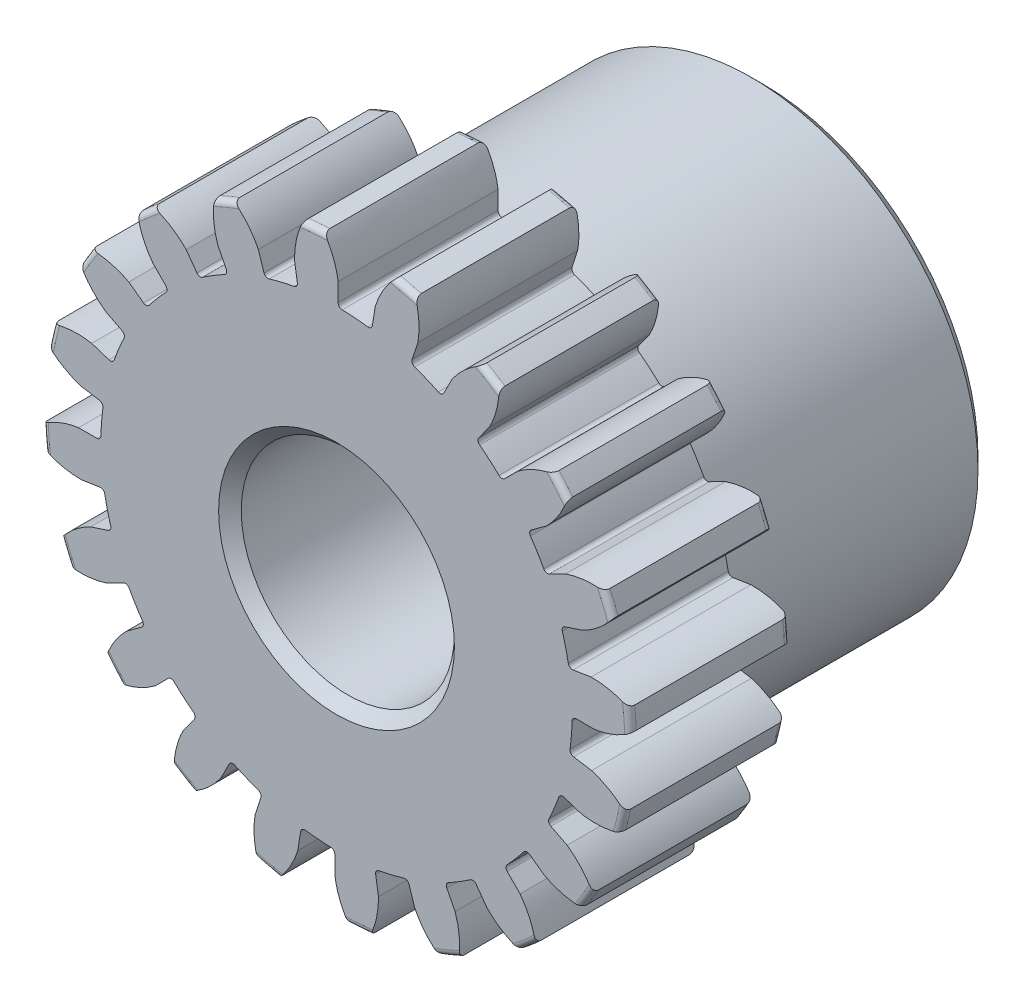
SolidWorks part; units mm, degrees
ref_plane "Front" through (0, 0, 0) normal (0, 0, 1) x (1, 0, 0)
ref_plane "Top" through (0, 0, 0) normal (0, 1, 0) x (1, 0, 0)
ref_plane "Right" through (0, 0, 0) normal (1, 0, 0) x (0, 0, -1)
sketch "Sketch1" plane through (0, 0, 0) normal (0, 0, 1) x (1, 0, 0)
  line L0 (-254, 0) -> (254, 0) construction
  circle A0 centre (0, 0) radius 8.763
  circle A1 centre (0, 0) radius 7.9375 construction
  circle A3 centre (0, 0) radius 7.0191 construction
  dimension "D1" = 0.9184
  dimension "OD" = 17.526
  dimension "Ptich Dia" = 15.875
  dimension "D2" = 1.7439
  dimension "Root Dia" = 14.0383
  dimension "D3" = 0.8255
  dimension "Number of Teeth" = 508
extrude "Boss-Extrude1" add sketch "Sketch1" against normal blind 4.7625
sketch "Sketch2" plane through (0, 0, 0) normal (1, 0, 0) x (0, 0, -1)
  line L0 (4.7625, 0) -> (12.7, 0)
  line L1 (4.7625, 0) -> (4.7625, 6.7469)
  line L2 (4.7625, 6.7469) -> (12.7, 6.7469)
  line L3 (12.7, 6.7469) -> (12.7, 0)
  point P5 (12.7, -6.7469)
  dimension "Face Wd" = 4.7625
  dimension "D Oa'll Wd" = 12.7
  dimension "B Hub Dia" = 13.4937
revolve "Revolve1" add sketch "Sketch2" angle 360 about L0
fillet "Fillet2" radius 0.1753 3 edges at (8.763, 0, -4.7625) (8.763, 0, 0) (6.7469, 0, -4.7625)
sketch "Sketch3" plane through (0, 0, 0) normal (0, 0, 1) x (1, 0, 0)
  line L0 (0, 0) -> (0, 8.763) construction
  line L1 (-1.9241, 7.4399) -> (0, 7.9375)
  line L2 (-9.5921, 7.9375) -> (9.5921, 7.9375) construction
  line L3 (-9.2865, 5.5358) -> (9.2865, 10.3392) construction
  line L4 (-1.9241, 7.4399) -> (0, 0) construction
  line L5 (-4.2708, 6.3886) -> (0, 0) construction
  line L6 (-4.2708, 6.3886) -> (-0.4919, 8.9149) construction
  line L7 (-1.3417, 7.5666) -> (0, 0) construction
  line L8 (-1.3417, 7.5666) -> (0.0282, 7.8095) construction
  arc A0 (-1.9241, 7.4399) -> (-4.2708, 6.3886) centre (0, 0) ccw
  circle A1 centre (0, 0) radius 7.9375 construction
  circle A2 centre (0, 0) radius 7.6847 construction
  arc A3 (-1.9241, 7.4399) -> (-1.3417, 7.5666) centre (0, 0) cw
  circle A4 centre (0, 0) radius 8.763 construction
  point P6 (0, 7.9375)
  dimension "D1" = 1.9874
  dimension "Pressure Angle" = 14.5
  dimension "D2" = 2.5836
  dimension "D3" = 4.5456
  dimension "D4" = 0.5962
  dimension "D5" = 1.3912
sketch "Sketch4" plane through (0, 0, 0) normal (0, 0, 1) x (1, 0, 0)
  line L0 (0, 0) -> (0.6209, 7.8886) construction
  line L1 (0.0488, 7.6845) -> (0.0488, 7.019)
  line L2 (0, 7.9375) -> (1.2417, 7.8398) construction
  line L3 (1.1539, 7.5975) -> (1.0498, 6.9402)
  line L4 (0.0488, 7.019) -> (0, 0) construction
  line L5 (0, 0) -> (0, 8.763) construction
  arc A0 (1.0498, 6.9402) -> (0.0488, 7.019) centre (0, 0) ccw
  arc A1 (0, 7.9375) -> (1.2417, 7.8398) centre (0, 0) cw construction
  circle A2 centre (0, 0) radius 7.9375 construction
  circle A3 centre (0, 0) radius 7.6847 construction
  circle A4 centre (0, 0) radius 7.0191 construction
  arc A5 (1.8804, 8.7282) -> (-0.4919, 8.9149) centre (0, 0) ccw
  spline S0 degree 2 poles (-0.4919, 8.9149) (-0.0446, 8.3548) (0.0488, 7.6845) knots 0 0 0 1 1 1
  spline S1 degree 2 poles (1.8804, 8.7282) (1.351, 8.2449) (1.1539, 7.5975) knots 0 0 0 1 1 1
  dimension "D1" = 1.2468
extrude "Cut-Extrude1" cut sketch "Sketch4" against normal through all
fillet "Fillet1" radius 0.1247 2 edges at (1.0498, 6.9402, -2.3812) (0.0488, 7.019, -2.3812)
pattern_circular "CirPattern1" count 20 over 360 about axis through (0, 0, -4.7625) along (0, 0, 1) of "Cut-Extrude1", "Fillet1"
sketch "Sketch5" plane through (0, 0, 0) normal (0, 0, 1) x (1, 0, 0)
  circle A0 centre (0, 0) radius 3.175
  circle A1 centre (0, 0) radius 5.5562 construction
  dimension "Bore Min" = 6.35
  dimension "Bore Max" = 11.1125
extrude "Cut-Extrude2" cut sketch "Sketch5" against normal through all
chamfer "Chamfer1" distance 0.3373 angle 45 3 edges at (6.7469, 0, -12.7) (3.175, 0, 0) (3.175, 0, -12.7)
sketch "Pitch Dia" plane through (0, 0, 0) normal (0, 0, 1) x (1, 0, 0)
  circle A0 centre (0, 0) radius 7.9375 construction
  circle A1 centre (0, 0) radius 7.9375
equation "\"D1@Boss-Extrude1\" = \"Face Wd@Sketch2\""
equation "\"D2@Sketch3\" = \"D1@Sketch3\"*1.3"
equation "\"D3@Sketch3\" = \"D1@Sketch3\"+\"D2@Sketch3\"-.001"
equation "\"D4@Sketch3\" = \"D1@Sketch3\"*.3"
equation "\"D5@Sketch3\" = \"D1@Sketch3\"-\"D4@Sketch3\""
equation "\"D1@Sketch4\" = 1.5708/(\"Number of Teeth@Sketch1\"/\"Ptich Dia@Sketch1\")"
equation "\"D1@Chamfer1\" = \"B Hub Dia@Sketch2\"*.025"
equation "\"D1@CirPattern1\" = \"Number of Teeth@Sketch1\""
equation "\"D1@Fillet1\" = \"D1@Sketch4\"*.1"
equation "\"D1@Fillet2\" = \"OD@Sketch1\"*.01"
equation "\"D1@Sketch1\" = 1.157/(\"Number of Teeth@Sketch1\"/\"Ptich Dia@Sketch1\")"
